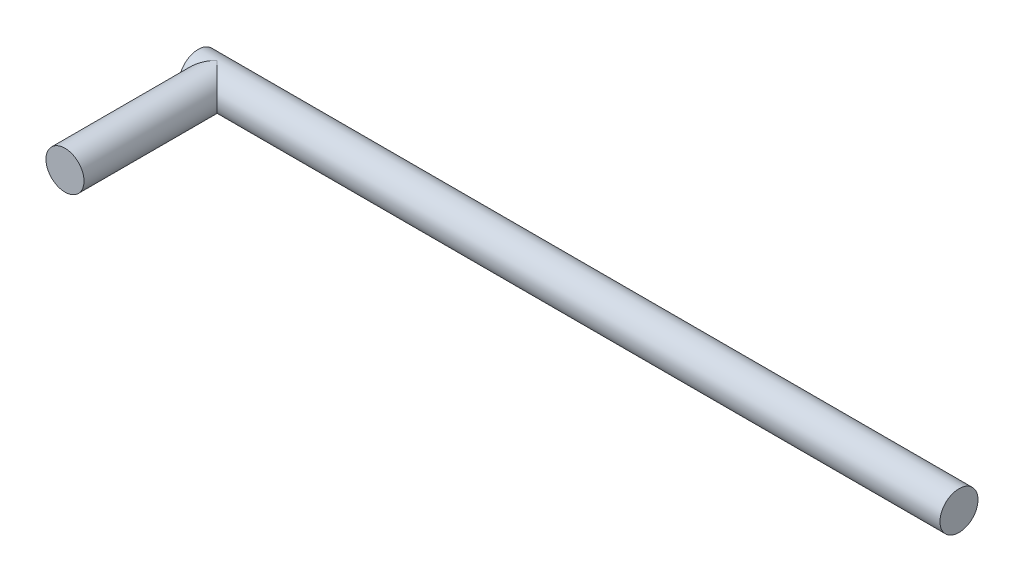
SolidWorks part; units mm, degrees
material "AISI 4340 Steel, annealed"
ref_plane "Front Plane" through (0, 0, 0) normal (0, 0, 1) x (1, 0, 0)
ref_plane "Top Plane" through (0, 0, 0) normal (0, 1, 0) x (1, 0, 0)
ref_plane "Right Plane" through (0, 0, 0) normal (1, 0, 0) x (0, 0, -1)
sketch "Sketch2" plane through (0, 0, 0) normal (1, 0, 0) x (0, 0, -1)
  circle A0 centre (0, 0) radius 1.27
  dimension "D1" = 2.54
extrude "Boss-Extrude1" add sketch "Sketch2" along normal blind 50.8
sketch "Sketch3" plane through (0, 0, 0) normal (0, 0, 1) x (1, 0, 0)
  line L0 (0, 1.27) -> (0, -1.27) construction
  line L1 (50.8, 1.27) -> (0, 1.27) construction
  circle A0 centre (1.27, 0) radius 1.27
  point P3 (0, 0)
  point P4 (0, 0)
  dimension "D1" = 2.54
extrude "Boss-Extrude2" add sketch "Sketch3" along normal blind 10.16
